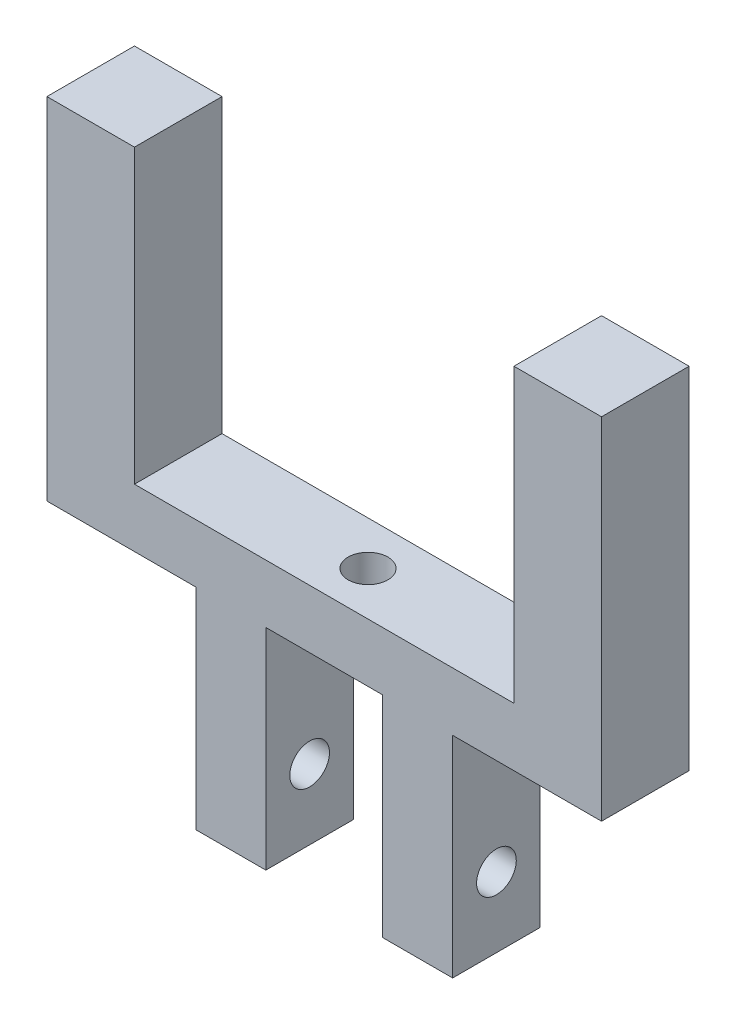
SolidWorks part; units mm, degrees
ref_plane "Plano frontal" through (0, 0, 0) normal (0, 0, 1) x (1, 0, 0)
ref_plane "Plano superior" through (0, 0, 0) normal (0, 1, 0) x (1, 0, 0)
ref_plane "Plano direito" through (0, 0, 0) normal (1, 0, 0) x (0, 0, -1)
sketch "Esboço1" plane through (0, 0, 0) normal (0, 0, 1) x (1, 0, 0)
  line L0 (-23.75, 0) -> (-23.75, -30)
  line L1 (-5, -40) -> (-5, -30)
  line L2 (-11, -48) -> (-5, -48)
  line L3 (-5, -48) -> (-5, -40)
  line L4 (-23.75, -30) -> (-11, -30)
  line L5 (-5, -30) -> (0, -30)
  line L6 (0, -30) -> (0, -25)
  line L7 (0, -25) -> (-16.25, -25)
  line L8 (-16.25, -25) -> (-16.25, 0)
  line L9 (-16.25, 0) -> (-23.75, 0)
  line L10 (0, 0) -> (0, -14.023) construction
  line L11 (-11, -48) -> (-11, -30)
  point P13 (-20, 0)
  point P41 (-5, -44)
  dimension "D1" = 7.5
  dimension "D2" = 40
  dimension "D3" = 25
  dimension "D4" = 5
  dimension "D5" = 0
  dimension "D6" = 6
  dimension "D7" = 10
  dimension "D8" = 14
  dimension "D9" = 8
extrude "Ressalto-extrusão1" add sketch "Esboço1" along normal blind 7.5
mirror "Espelhar1" about plane through (0, -30, 7.5) normal (-1, 0, 0) of "Ressalto-extrusão1"
sketch "Esboço2" plane through (11, 0, 0) normal (1, 0, 0) x (0, 0, -1)
  line L0 (-7.5, -48) -> (0, -48) construction
  circle A0 centre (-3.75, -42) radius 1.7
  point P5 (-3.75, -48)
  dimension "D2" = 3.4
  dimension "D1" = 6
extrude "Corte-extrusão1" cut sketch "Esboço2" against normal through all
sketch "Esboço3" plane through (0, 0, 0) normal (0, 1, 0) x (1, 0, 0)
  line L0 (-16.25, -7.5) -> (-16.25, 0) construction
  circle A0 centre (0, -3.75) radius 1.7
  point P5 (-16.25, -3.75)
  dimension "D1" = 3.4
extrude "Corte-extrusão2" cut sketch "Esboço3" against normal through all
